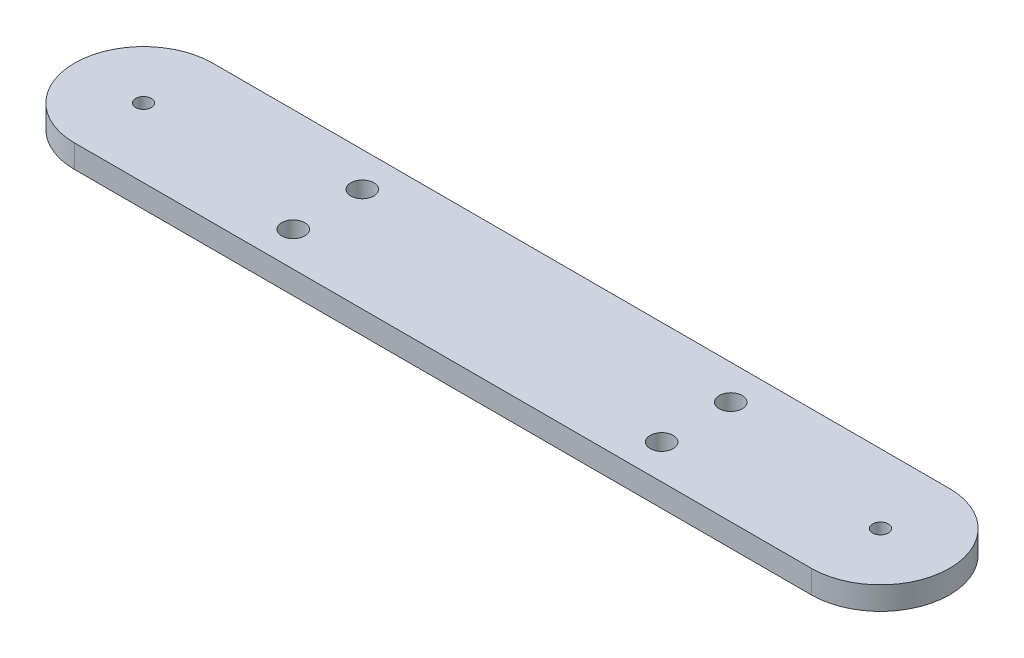
SolidWorks part; units mm, degrees
ref_plane "Front Plane" through (0, 0, 0) normal (0, 0, 1) x (1, 0, 0)
ref_plane "Top Plane" through (0, 0, 0) normal (0, 1, 0) x (1, 0, 0)
ref_plane "Right Plane" through (0, 0, 0) normal (1, 0, 0) x (0, 0, -1)
sketch "Sketch1" plane through (0, 0, 0) normal (0, 1, 0) x (1, 0, 0)
  line L0 (0, 0) -> (203.2, 0) construction
  line L1 (0, 19.05) -> (203.2, 19.05)
  line L2 (0, -19.05) -> (203.2, -19.05)
  line L3 (50.8, 9.525) -> (50.8, -9.525) construction
  line L4 (50.8, -9.525) -> (152.4, -9.525) construction
  line L5 (152.4, -9.525) -> (152.4, 9.525) construction
  line L6 (152.4, 9.525) -> (50.8, 9.525) construction
  arc A0 (0, 19.05) -> (0, -19.05) centre (0, 0) ccw
  arc A1 (203.2, -19.05) -> (203.2, 19.05) centre (203.2, 0) ccw
  circle A2 centre (0, 0) radius 2.1828
  circle A3 centre (203.2, 0) radius 2.1828
  circle A4 centre (50.8, 9.525) radius 3.175
  circle A5 centre (152.4, 9.525) radius 3.175
  circle A6 centre (152.4, -9.525) radius 3.175
  circle A7 centre (50.8, -9.525) radius 3.175
  point P3 (101.6, 0)
  point P15 (101.6, 9.525)
  dimension "D3" = 4.3656
  dimension "D4" = 4.3656
  dimension "D8" = 6.35
  dimension "D9" = 6.35
  dimension "D10" = 6.35
  dimension "D11" = 6.35
  dimension "D1" = 203.2
  dimension "D2" = 38.1
  dimension "D5" = 9.525
  dimension "D6" = 9.525
  dimension "D7" = 101.6
extrude "Boss-Extrude1" add sketch "Sketch1" along normal blind 6.35
